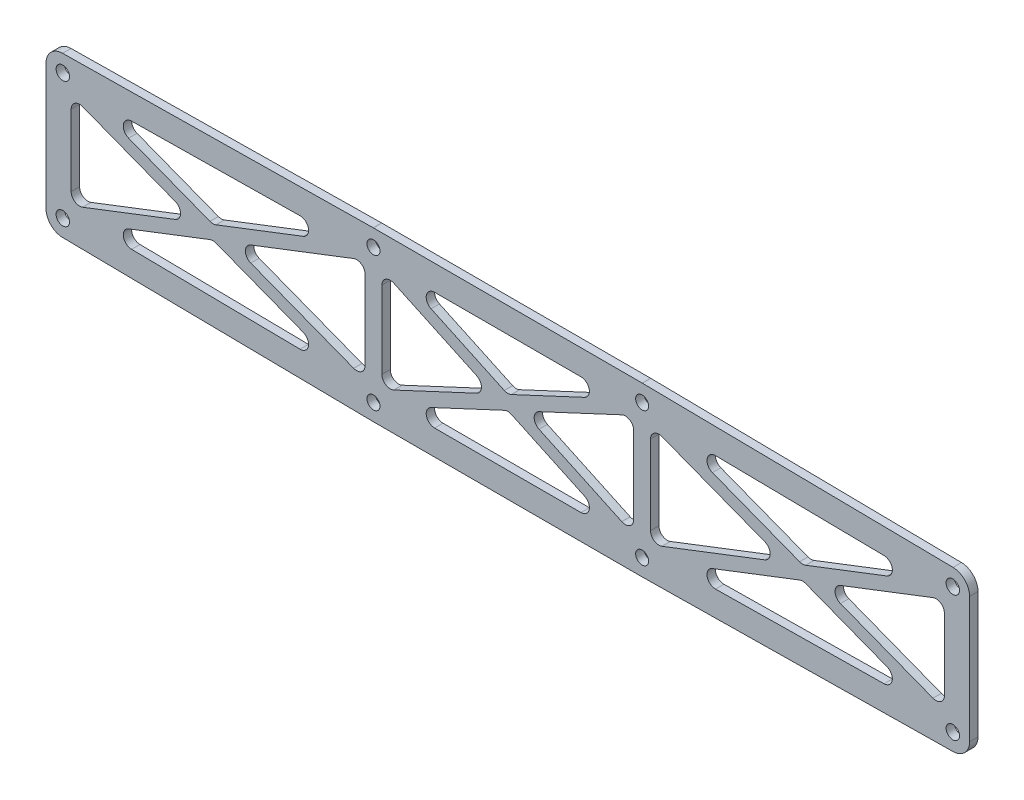
SolidWorks part; units mm, degrees
material "Thornel Mat VMA"
ref_plane "前视基准面" through (0, 0, 0) normal (0, 0, 1) x (1, 0, 0)
ref_plane "上视基准面" through (0, 0, 0) normal (0, 1, 0) x (1, 0, 0)
ref_plane "右视基准面" through (0, 0, 0) normal (1, 0, 0) x (0, 0, -1)
sketch "草图1" plane through (0, 0, 0) normal (0, 0, 1) x (1, 0, 0)
  line L1 (-116, -26) -> (116, -26)
  line L2 (-116, -26) -> (-116, 26)
  line L3 (-116, 26) -> (116, 26)
  line L4 (116, -26) -> (116, 26)
  line L5 (0, 26) -> (0, -26) construction
  line L6 (-116, 0) -> (116, 0) construction
  point P0 (0, 0)
  dimension "D1" = 232
  dimension "D2" = 52
extrude "凸台-拉伸1" add sketch "草图1" along normal blind 2
sketch "草图3" plane through (0, 0, 2) normal (0, 0, 1) x (1, 0, 0)
  circle A0 centre (32, -16) radius 1.55 construction
  circle A1 centre (32, 16) radius 1.55 construction
  circle A2 centre (-32, 16) radius 1.55 construction
  circle A3 centre (-32, -16) radius 1.55 construction
  circle A4 centre (32, -16) radius 1.55
  circle A5 centre (32, 16) radius 1.55
  circle A6 centre (-32, 16) radius 1.55
  circle A7 centre (-32, -16) radius 1.55
extrude "切除-拉伸2" cut sketch "草图3" against normal blind 10
fillet "圆角1" radius 3 4 edges at (116, -26, 1) (116, 26, 1) (-116, 26, 1) (-116, -26, 1)
sketch "草图8" plane through (0, 0, 2) normal (0, 0, 1) x (1, 0, 0)
  line L0 (0, 0) -> (50000, 0) construction
  line L1 (-106, 26) -> (-106, -26) construction
  line L4 (113, 26) -> (-113, 26) construction
  line L5 (-113, -26) -> (113, -26) construction
  line L6 (-116, 23) -> (-116, -23) construction
  circle A0 centre (-106, 15) radius 1.6
  circle A1 centre (-106, -15) radius 1.6
  dimension "D3" = 3.2
  dimension "D4" = 30
  dimension "D1" = 52
  dimension "D2" = 10
extrude "切除-拉伸6" cut sketch "草图8" against normal blind 10
mirror "镜向1" about plane through (0, 0, 0) normal (1, 0, 0) of "切除-拉伸6"
sketch "草图9" plane through (0, 0, 2) normal (0, 0, 1) x (1, 0, 0)
  line L0 (-110, 15) -> (-110, -15)
  line L1 (110, 15) -> (110, -15)
  line L2 (-32, -20) -> (32, -20)
  line L3 (-32, 20) -> (32, 20)
  line L4 (-106.054, 18.9996) -> (-32.054, 19.9996)
  line L5 (32.054, 19.9996) -> (106.054, 18.9996)
  line L6 (-106.054, -18.9996) -> (-32.054, -19.9996)
  line L7 (32.054, -19.9996) -> (106.054, -18.9996)
  line L16 (-113, -26) -> (113, -26)
  line L17 (116, -23) -> (116, 23)
  line L18 (113, 26) -> (-113, 26)
  line L19 (-116, 23) -> (-116, -23)
  line L20 (-113, -26) -> (113, -26)
  line L21 (116, -23) -> (116, 23)
  line L22 (113, 26) -> (-113, 26)
  line L23 (-116, 23) -> (-116, -23)
  circle A0 centre (-106, 15) radius 4
  circle A1 centre (106, 15) radius 4
  circle A2 centre (106, -15) radius 4
  circle A3 centre (-106, -15) radius 4
  circle A4 centre (-32, 16) radius 4
  circle A5 centre (32, 16) radius 4
  circle A6 centre (-32, -16) radius 4
  circle A7 centre (32, -16) radius 4
  arc A16 (113, -26) -> (116, -23) centre (113, -23) ccw
  arc A17 (116, 23) -> (113, 26) centre (113, 23) ccw
  arc A18 (-113, 26) -> (-116, 23) centre (-113, 23) ccw
  arc A19 (-116, -23) -> (-113, -26) centre (-113, -23) ccw
  arc A20 (113, -26) -> (116, -23) centre (113, -23) ccw
  arc A21 (116, 23) -> (113, 26) centre (113, 23) ccw
  arc A22 (-113, 26) -> (-116, 23) centre (-113, 23) ccw
  arc A23 (-116, -23) -> (-113, -26) centre (-113, -23) ccw
  line M16 (-113, -26) -> (113, -26)
  arc M17 (113, -26) -> (116, -23) centre (113, -23) ccw
  line M18 (116, -23) -> (116, 23)
  arc M19 (116, 23) -> (113, 26) centre (113, 23) ccw
  line M20 (113, 26) -> (-113, 26)
  arc M21 (-113, 26) -> (-116, 23) centre (-113, 23) ccw
  line M22 (-116, 23) -> (-116, -23)
  arc M23 (-116, -23) -> (-113, -26) centre (-113, -23) ccw
  dimension "D1" = 8
  dimension "D2" = 0
extrude "切除-拉伸7" cut sketch "草图9" against normal mid plane 10 contours A7 L2 A6 L6 A3 L0 A0 L4 A4 L3 A5 L5 A1 L1 A2 L7 M23 M16 M17 M18 M19 M20 M21 M22
sketch "草图10" plane through (0, 0, 2) normal (0, 0, 1) x (1, 0, 0)
  line L0 (-32, 16) -> (-32, -16) construction
  line L1 (30, -14) -> (-30, -14)
  line L2 (30, -14) -> (30, 14)
  line L3 (30, 14) -> (-30, 14)
  line L4 (-30, -14) -> (-30, 14)
  line L5 (30, -14) -> (-30, 14) construction
  line L6 (30, 14) -> (-30, -14) construction
  line L7 (32, 20) -> (-32, 20) construction
  line L8 (-34, 13.9728) -> (-104, 13.0268)
  line L9 (-104, 13.0268) -> (-104, -13.0268)
  line L10 (-104, -13.0268) -> (-34, -13.9728)
  line L11 (-34, -13.9728) -> (-34, 13.9728)
  line L12 (0, 0) -> (50000, 0) construction
  line L13 (-32.054, 19.9996) -> (-106.054, 18.9996) construction
  line L15 (-110, -15) -> (-110, 15) construction
  line L16 (-104, 13.0268) -> (-34, -13.9728) construction
  line L17 (-104, -13.0268) -> (-34, 13.9728) construction
  line L18 (-103.4602, -14.4263) -> (-33.4602, 12.5733)
  line L19 (-104.5398, 11.6273) -> (-34.5398, -15.3723)
  line L20 (30.6343, -12.6407) -> (-29.3657, 15.3593)
  line L21 (29.3657, 15.3593) -> (-30.6343, -12.6407)
  line L22 (-104.5398, -11.6273) -> (-34.5398, 15.3723)
  line L23 (-103.4602, 14.4263) -> (-33.4602, -12.5733)
  line L24 (29.3657, -15.3593) -> (-30.6343, 12.6407)
  line L25 (30.6343, 12.6407) -> (-29.3657, -15.3593)
  line L26 (0, 0) -> (0, -50000) construction
  line L27 (104, -13.0268) -> (34, 13.9728) construction
  line L28 (104, 13.0268) -> (34, -13.9728) construction
  line L29 (0, 0) -> (-50000, 0) construction
  line L30 (32, 16) -> (32, -16) construction
  line L31 (103.4602, 14.4263) -> (33.4602, -12.5733)
  line L32 (104.5398, -11.6273) -> (34.5398, 15.3723)
  line L33 (104.5398, 11.6273) -> (34.5398, -15.3723)
  line L34 (103.4602, -14.4263) -> (33.4602, 12.5733)
  line L35 (34, -13.9728) -> (34, 13.9728)
  line L36 (104, -13.0268) -> (34, -13.9728)
  line L37 (104, 13.0268) -> (104, -13.0268)
  line L38 (34, 13.9728) -> (104, 13.0268)
  point P0 (0, 0)
  dimension "D1" = 2
  dimension "D2" = 6
  dimension "D3" = 6
  dimension "D4" = 6
  dimension "D5" = 2
  dimension "D6" = 1.5
  dimension "D7" = 1.5
extrude "切除-拉伸8" cut sketch "草图10" against normal mid plane 10 contours L8 L23 L22 | L9 L22 L19 | L19 L18 L10 | L18 L23 L11 | L21 L24 L4 | L21 L3 L20 | L2 L25 L20 | L35 L31 L34 | L38 L32 L31 | L37 L33 L32 | L36 L34 L33 | L24 L25 L1
fillet "圆角2" radius 2 36 edges at (66.058, 0, 1) (34, -12.3651, 1) (34, 12.3651, 1) (70.2262, 1.6077, 1) (38.3195, 13.9144, 1) (99.9729, 13.0813, 1) (26.4529, 14, 1) (0, 1.6553, 1) (-99.9729, -13.0813, 1) (-70.2262, -1.6077, 1) (-38.3195, -13.9144, 1) (-34, -12.3651, 1) (-66.058, 0, 1) (-34, 12.3651, 1) (-30, 12.3447, 1) (-3.5471, 0, 1) (-30, -12.3447, 1) (70.2262, -1.6077, 1) (99.9729, -13.0813, 1) (38.3195, -13.9144, 1) (74.3944, 0, 1) (104, 11.4191, 1) (104, -11.4191, 1) (-38.3195, 13.9144, 1) (-70.2262, 1.6077, 1) (-99.9729, 13.0813, 1) (26.4529, -14, 1) (-26.4529, -14, 1) (0, -1.6553, 1) (-104, 11.4191, 1) (-74.3944, 0, 1) (-104, -11.4191, 1) (30, -12.3447, 1) (3.5471, 0, 1) (30, 12.3447, 1) (-26.4529, 14, 1)
